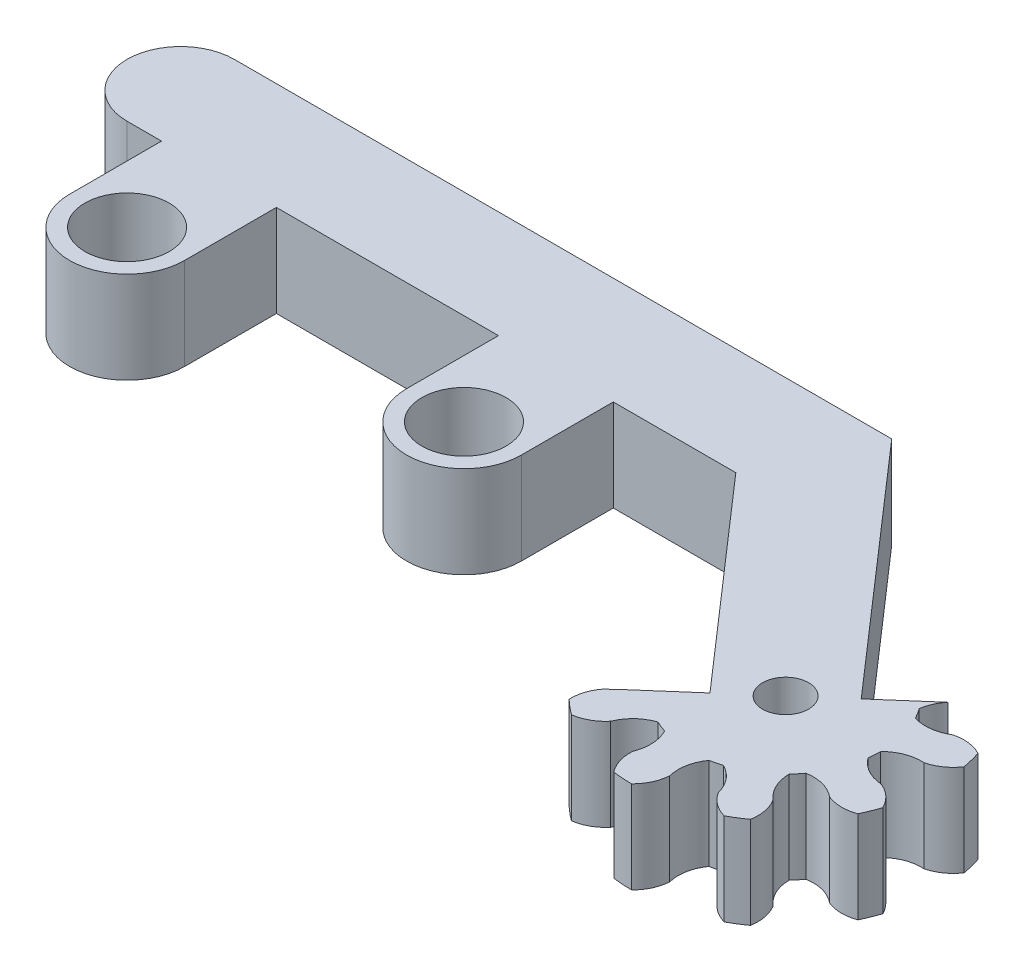
SolidWorks part; units mm, degrees
ref_plane "Alzado" through (0, 0, 0) normal (0, 0, 1) x (1, 0, 0)
ref_plane "Planta" through (0, 0, 0) normal (0, 1, 0) x (1, 0, 0)
ref_plane "Vista lateral" through (0, 0, 0) normal (1, 0, 0) x (0, 0, -1)
sketch "Croquis1" plane through (0, 0, 0) normal (0, 1, 0) x (1, 0, 0)
  line L1 (42.931, 0) -> (56.6365, -15.6981)
  line L2 (51.3635, -20.3019) -> (39.75, -7)
  line L3 (39.75, -7) -> (31.75, -7)
  line L4 (31.75, -7) -> (31.75, -13)
  line L5 (24.25, -13) -> (24.25, -7)
  line L6 (24.25, -7) -> (9.75, -7)
  line L7 (9.75, -7) -> (9.75, -13)
  line L8 (2.25, -13) -> (2.25, -7)
  line L9 (2.25, -7) -> (0, -7)
  line L11 (0, 0) -> (42.931, 0)
  line L12 (28, -13) -> (40.1019, -13) construction
  arc A0 (56.6365, -15.6981) -> (51.3635, -20.3019) centre (54, -18) cw
  arc A1 (31.75, -13) -> (24.25, -13) centre (28, -13) cw
  arc A2 (9.75, -13) -> (2.25, -13) centre (6, -13) cw
  arc A3 (0, -7) -> (0, 0) centre (0, -3.5) cw
  circle A4 centre (28, -13) radius 2.75
  circle A5 centre (6, -13) radius 2.75
  dimension "D4" = 5.5
  dimension "D8" = 5.5
  dimension "D1" = 7
  dimension "D2" = 7
  dimension "D3" = 7.5
  dimension "D5" = 7.5
  dimension "D6" = 22
  dimension "D7" = 6
  dimension "D9" = 6
  dimension "D10" = 5
  dimension "D11" = 8
  dimension "D12" = 26
extrude "Saliente-Extruir1" add sketch "Croquis1" along normal blind 6
sketch "Croquis2" plane through (0, 6, 0) normal (0, 1, 0) x (1, 0, 0)
  circle A0 centre (54, -18) radius 1.5
  dimension "D1" = 3
extrude "Cortar-Extruir1" cut sketch "Croquis2" against normal through all
sketch "Croquis3" plane through (0, 6, 0) normal (0, 1, 0) x (1, 0, 0)
  line L1 (56.6365, -15.6981) -> (61.533, -11.4232)
  line L3 (51.3635, -20.3019) -> (46.467, -24.5768)
  arc A0 (46.467, -24.5768) -> (61.533, -11.4232) centre (54, -18) ccw
  arc A1 (51.3635, -20.3019) -> (56.6365, -15.6981) centre (54, -18) ccw
  arc A2 (51.3635, -20.3019) -> (56.6365, -15.6981) centre (54, -18) ccw construction
  arc A3 (56.6365, -15.6981) -> (51.3635, -20.3019) centre (54, -18) cw
  arc M18 (51.3635, -20.3019) -> (56.6365, -15.6981) centre (54, -18) ccw
  dimension "D1" = 20
extrude "Saliente-Extruir2" add sketch "Croquis3" against normal blind 6 contours L3 A0 L1 M18
sketch "Croquis4" plane through (0, 6, 0) normal (0, 1, 0) x (1, 0, 0)
  line L0 (47.7224, -23.4808) -> (48.342, -22.9398) construction
  line L1 (54, -18) -> (48.5077, -20.9833) construction
  line L2 (51.3635, -20.3019) -> (46.467, -24.5768) construction
  line L3 (54, -18) -> (51.3102, -23.6418) construction
  arc A0 (44.4719, -21.0357) -> (47.1163, -25.2536) centre (54, -18) ccw
  arc A3 (44.4719, -21.0357) -> (46.3317, -21.2626) centre (45.6979, -18.7225) ccw
  arc A4 (47.7224, -23.4808) -> (48.9219, -21.6438) centre (46.3317, -21.2626) ccw
  arc A6 (47.7224, -23.4808) -> (47.1163, -25.2536) centre (49.7327, -25.158) ccw
  arc A7 (48.5077, -20.9833) -> (48.9219, -21.6438) centre (54, -18) ccw
  arc A8 (48.076, -26.0564) -> (52.6946, -27.9144) centre (54, -18) ccw
  arc A9 (48.5077, -20.9833) -> (46.3317, -21.2626) centre (47.7224, -23.4808) ccw
  arc A10 (52.1428, -26.1239) -> (52.6946, -27.9144) centre (54.755, -26.2992) ccw
  arc A11 (52.1428, -26.1239) -> (52.0335, -23.9328) centre (49.714, -25.1468) ccw
  arc A12 (51.3102, -23.6418) -> (52.0335, -23.9328) centre (54, -18) ccw
  arc A13 (51.3102, -23.6418) -> (49.714, -25.1468) centre (52.1428, -26.1239) ccw
  arc A14 (48.076, -26.0564) -> (49.714, -25.1468) centre (47.7081, -23.4644) ccw
  arc A15 (53.9428, -27.9998) -> (58.7715, -26.7882) centre (54, -18) ccw
  arc A16 (57.2726, -25.664) -> (58.7715, -26.7882) centre (59.489, -24.2704) ccw
  arc A17 (57.2726, -25.664) -> (55.8963, -23.9556) centre (54.7333, -26.3012) ccw
  arc A18 (55.1401, -24.1453) -> (55.8963, -23.9556) centre (54, -18) ccw
  arc A19 (55.1401, -24.1453) -> (54.7333, -26.3012) centre (57.2726, -25.664) ccw
  arc A20 (53.9428, -27.9998) -> (54.7333, -26.3012) centre (52.1216, -26.119) ccw
  arc A21 (59.8315, -26.1237) -> (63.0258, -22.3052) centre (54, -18) ccw
  arc A22 (61.1524, -22.2767) -> (63.0258, -22.3052) centre (62.1263, -19.8465) ccw
  arc A23 (61.1524, -22.2767) -> (59.0347, -21.7036) centre (59.4726, -24.2848) ccw
  arc A24 (58.5345, -22.3016) -> (59.0347, -21.7036) centre (54, -18) ccw
  arc A25 (58.5345, -22.3016) -> (59.4726, -24.2848) centre (61.1524, -22.2767) ccw
  arc A26 (59.8315, -26.1237) -> (59.4726, -24.2848) centre (57.2526, -25.6725) ccw
  arc A27 (63.4927, -21.1445) -> (63.8326, -16.1778) centre (54, -18) ccw
  arc A28 (62.3002, -17.2558) -> (63.8326, -16.1778) centre (61.6597, -14.7173) ccw
  arc A29 (62.3002, -17.2558) -> (60.2501, -18.0369) centre (62.1215, -19.8678) ccw
  arc A30 (60.1969, -18.8147) -> (60.2501, -18.0369) centre (54, -18) ccw
  arc A31 (60.1969, -18.8147) -> (62.1215, -19.8678) centre (62.3002, -17.2558) ccw
  arc A32 (63.4927, -21.1445) -> (62.1215, -19.8678) centre (61.1412, -22.2954) ccw
  arc A33 (63.5281, -14.9643) -> (60.8837, -10.7464) centre (54, -18) ccw
  arc A34 (60.2776, -12.5192) -> (60.8837, -10.7464) centre (58.2673, -10.842) ccw
  arc A35 (60.2776, -12.5192) -> (59.0781, -14.3562) centre (61.6683, -14.7374) ccw
  arc A36 (59.4923, -15.0167) -> (59.0781, -14.3562) centre (54, -18) ccw
  arc A37 (59.4923, -15.0167) -> (61.6683, -14.7374) centre (60.2776, -12.5192) ccw
  arc A38 (63.5281, -14.9643) -> (61.6683, -14.7374) centre (62.3021, -17.2775) ccw
  dimension "D1" = 20
  dimension "D2" = 6
  dimension "D3" = 36
  dimension "D5" = 5.2361
  dimension "D4" = 6.2502
extrude "Cortar-Extruir2" cut sketch "Croquis4" against normal through all
ref_plane "Plano1" through (54, 0, 0) normal (1, 0, 0) x (0, 0, -1)
sketch "Croquis5" plane through (54, 0, 0) normal (1, 0, 0) x (0, 0, -1)
  line L0 (-18, 11.6873) -> (-18, -5.413) construction
  line L1 (-18, 0) -> (-18, 6) construction
  point P2 (-18.0761, 9.4895)
  point P3 (-18.0811, 4.6262)
  point P6 (-18, 7.9609)
  point P7 (-18, -5.413)
  point P8 (-18, 11.6873)
